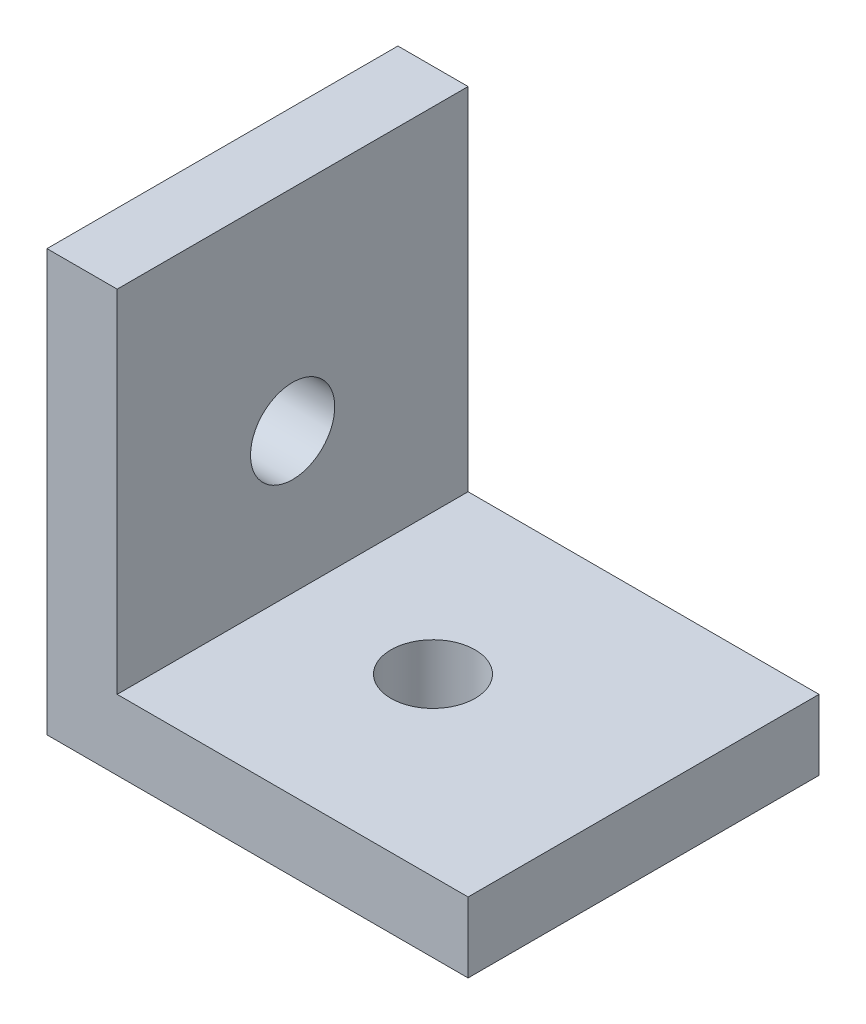
SolidWorks part; units mm, degrees
ref_plane "Front Plane" through (0, 0, 0) normal (0, 0, 1) x (1, 0, 0)
ref_plane "Top Plane" through (0, 0, 0) normal (0, 1, 0) x (1, 0, 0)
ref_plane "Right Plane" through (0, 0, 0) normal (1, 0, 0) x (0, 0, -1)
sketch "Sketch1" plane through (0, 0, 0) normal (0, 0, 1) x (1, 0, 0)
  line L0 (0, 0) -> (40.701, 40.701) construction
  line L1 (0, 0) -> (0, 30)
  line L2 (0, 30) -> (5, 30)
  line L3 (5, 30) -> (5, 5)
  line L4 (0, 0) -> (30, 0)
  line L5 (30, 5) -> (5, 5)
  line L6 (30, 0) -> (30, 5)
  dimension "D1" = 45
  dimension "D2" = 5
  dimension "D3" = 30
extrude "Boss-Extrude1" add sketch "Sketch1" along normal mid plane 25
sketch "Sketch2" plane through (0, 0, 0) normal (-1, 0, 0) x (0, 0, 1)
  line L1 (12.5, 30) -> (12.5, 0) construction
  line L2 (12.5, 0) -> (-12.5, 0) construction
  circle A0 centre (0, 15) radius 3
  point P4 (12.5, 15)
  point P7 (0, 0)
  dimension "D1" = 6
extrude "Cut-Extrude1" cut sketch "Sketch2" against normal through all
sketch "Sketch3" plane through (0, 0, 0) normal (0, -1, 0) x (0, 0, 1)
  line L0 (12.5, 0) -> (12.5, -30) construction
  line L3 (12.5, 0) -> (-12.5, 0) construction
  circle A0 centre (0, -15) radius 3
  point P4 (12.5, -15)
  point P7 (0, 0)
  dimension "D1" = 6
extrude "Cut-Extrude2" cut sketch "Sketch3" against normal through all
